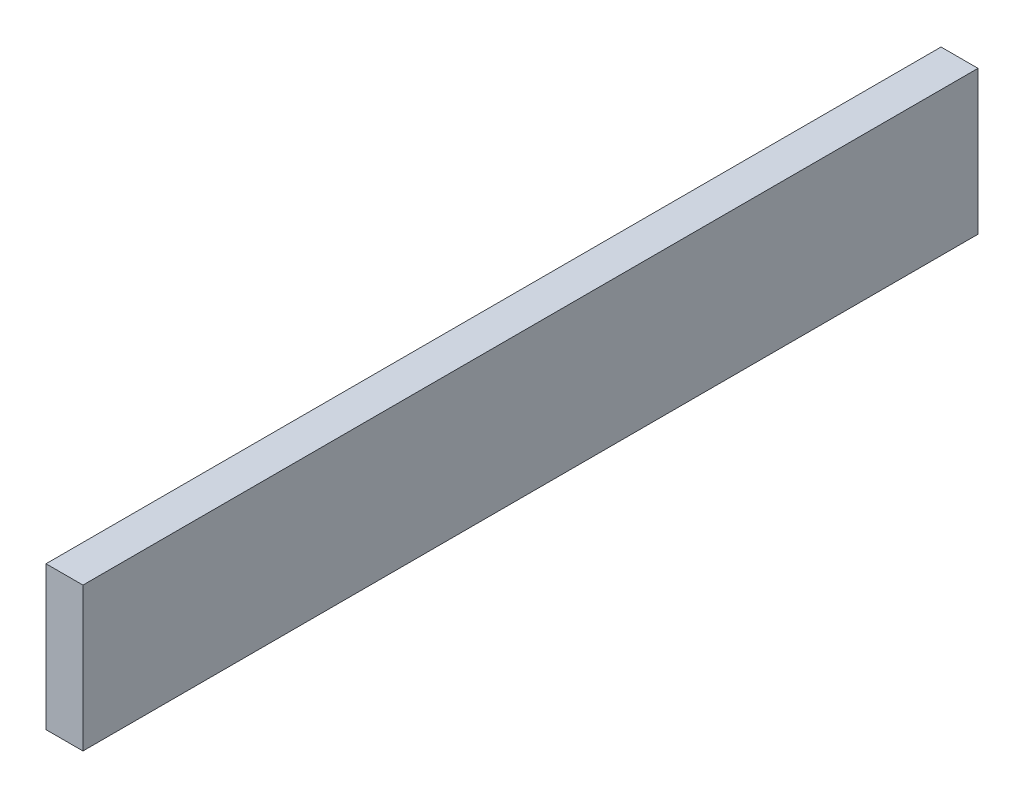
SolidWorks part; units mm, degrees
ref_plane "Front Plane" through (0, 0, 0) normal (0, 0, 1) x (1, 0, 0)
ref_plane "Top Plane" through (0, 0, 0) normal (0, 1, 0) x (1, 0, 0)
ref_plane "Right Plane" through (0, 0, 0) normal (1, 0, 0) x (0, 0, -1)
sketch "Sketch1" plane through (0, 0, 0) normal (1, 0, 0) x (0, 0, -1)
  line L1 (0, 0) -> (436, 0)
  line L2 (0, 0) -> (0, 70)
  line L3 (0, 70) -> (436, 70)
  line L4 (436, 0) -> (436, 70)
  dimension "D1" = 436
  dimension "D2" = 70
extrude "Boss-Extrude1" add sketch "Sketch1" along normal blind 18
